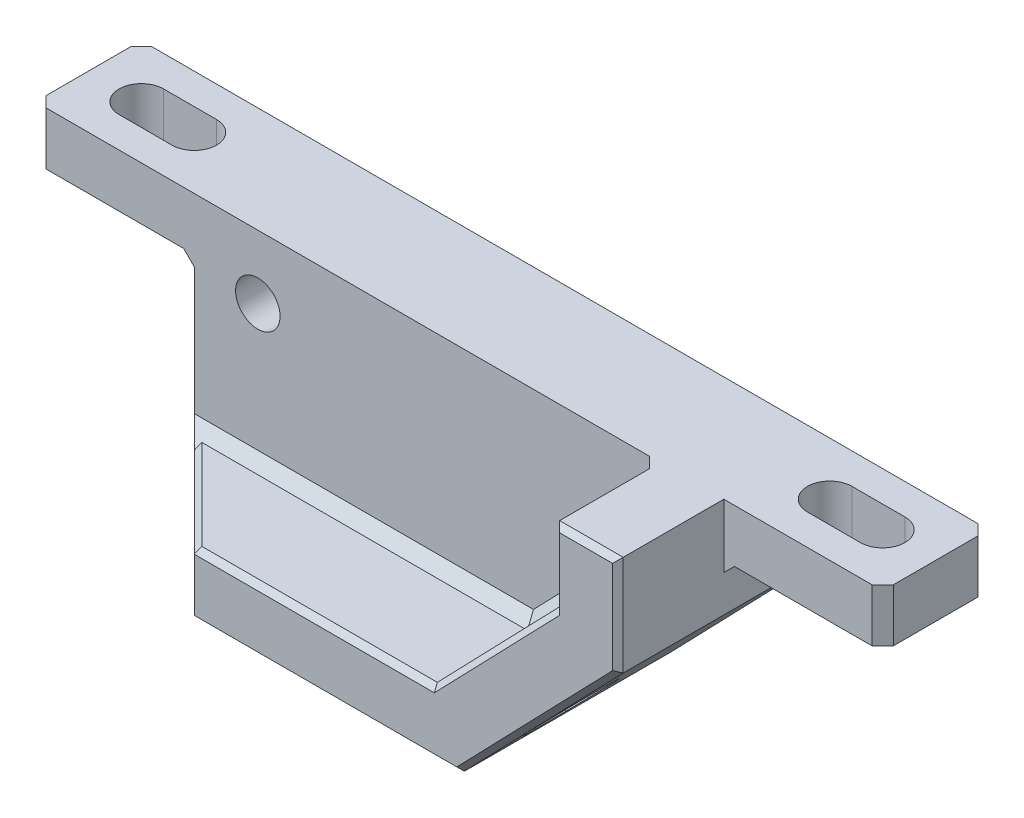
SolidWorks part; units mm, degrees
material "PET"
ref_plane "Přední rovina" through (0, 0, 0) normal (0, 0, 1) x (1, 0, 0)
ref_plane "Horní rovina" through (0, 0, 0) normal (0, 1, 0) x (1, 0, 0)
ref_plane "Pravá rovina" through (0, 0, 0) normal (1, 0, 0) x (0, 0, -1)
sketch "Skica1" plane through (0, 0, 0) normal (0, 0, 1) x (1, 0, 0)
  line L1 (0, 0) -> (50, 0)
  line L2 (0, 0) -> (0, 25)
  line L3 (0, 25) -> (50, 25)
  line L4 (50, 0) -> (50, 25)
  line L5 (0, 0) -> (50, 25) construction
  line L6 (0, 25) -> (50, 0) construction
  point P4 (25, 12.5)
  dimension "D1" = 25
  dimension "D2" = 50
extrude "Přidat vysunutím1" add sketch "Skica1" along normal blind 10
sketch "Skica2" plane through (0, 0, 10) normal (0, 0, 1) x (1, 0, 0)
  line L0 (0, 0) -> (35, 0)
  line L1 (0, 0) -> (50, 0) construction
  line L2 (35, 0) -> (50, 15.533)
  line L3 (50, 0) -> (50, 25) construction
  line L5 (44, 17.9571) -> (32.4532, 6)
  line L6 (0, 0) -> (0, 6)
  line L7 (0, 25) -> (0, 0) construction
  line L8 (0, 6) -> (32.4532, 6)
  line L9 (44, 25) -> (44, 17.9571)
  line L10 (50, 25) -> (0, 25) construction
  line L11 (44, 25) -> (50, 25)
  line L13 (50, 15.533) -> (50, 25)
  dimension "D1" = 6
  dimension "D2" = 6
  dimension "D3" = 46
  dimension "D4" = 35
  dimension "D5" = 6
extrude "Přidat vysunutím2" add sketch "Skica2" along normal blind 10
sketch "Skica3" plane through (0, 0, 10) normal (0, 0, 1) x (1, 0, 0)
  line L0 (0, 25) -> (0, 6) construction
  line L1 (44, 25) -> (0, 25) construction
  circle A0 centre (6, 19) radius 2.1
  dimension "D1" = 4.2
  dimension "D2" = 6
  dimension "D3" = 6
extrude "Odebrat vysunutím1" cut sketch "Skica3" against normal blind 10
sketch "Skica4" plane through (0, 0, 10) normal (0, 0, 1) x (1, 0, 0)
  line L3 (50, 15.533) -> (35, 0)
  line L4 (35, 0) -> (50, 0)
  line L5 (50, 0) -> (50, 15.533)
  line L6 (50, 15.533) -> (35, 0)
  line L7 (35, 0) -> (50, 0)
  line L8 (50, 0) -> (50, 15.533)
  dimension "D1" = 0
extrude "Odebrat vysunutím2" cut sketch "Skica4" against normal up to surface (10 mm away) up to face at (8.1, 19, 0)
sketch "Skica5" plane through (18.1107, -17.4893, 0) normal (0.7193, -0.6947, 0) x (0, 0, -1)
  line L3 (-20, 24.313) -> (0, 24.313) construction
  line L4 (-20, 24.313) -> (-20, 45.9064) construction
  circle A0 centre (-15, 32.313) radius 2.1
  dimension "D1" = 8
  dimension "D3" = 4.2
  dimension "D2" = 5
extrude "Odebrat vysunutím3" cut sketch "Skica5" against normal blind 10
sketch "Skica6" plane through (0, 25, 0) normal (0, 1, 0) x (1, 0, 0)
  line L0 (50, -20) -> (50, 0) construction
  line L5 (0, -10) -> (-15, -10)
  line L6 (0, -10) -> (0, 0)
  line L11 (0, 0) -> (-15, 0)
  line L12 (-15, -10) -> (-15, 0)
  line L13 (0, -10) -> (-15, 0) construction
  line L14 (0, 0) -> (-15, -10) construction
  line L15 (50, -10) -> (65, -10)
  line L16 (50, -10) -> (50, 0)
  line L17 (50, 0) -> (65, 0)
  line L18 (65, -10) -> (65, 0)
  line L19 (50, -10) -> (65, 0) construction
  line L20 (50, 0) -> (65, -10) construction
  line L21 (50, 0) -> (0, 0) construction
  point P4 (-7.5, -5)
  point P10 (57.5, -5)
  dimension "D3" = 15
  dimension "D1" = 10
  dimension "D2" = 15
  dimension "D4" = 10
extrude "Přidat vysunutím3" add sketch "Skica6" against normal blind 5
sketch "Skica9" plane through (18.1107, -17.4893, 0) normal (0.7193, -0.6947, 0) x (0, 0, -1)
  line L1 (-19.1569, 32.313) -> (-17.0785, 28.713)
  line L2 (-17.0785, 28.713) -> (-12.9215, 28.713)
  line L3 (-12.9215, 28.713) -> (-10.8431, 32.313)
  line L4 (-10.8431, 32.313) -> (-12.9215, 35.913)
  line L5 (-12.9215, 35.913) -> (-17.0785, 35.913)
  line L6 (-17.0785, 35.913) -> (-19.1569, 32.313)
  circle A0 centre (-15, 32.313) radius 3.6 construction
  dimension "D1" = 7.2
extrude "Odebrat vysunutím5" cut sketch "Skica9" against normal blind 3.5
sketch "Skica10" plane through (0, 0, 0) normal (0, 0, -1) x (-1, 0, 0)
  line L7 (-6, 23.1569) -> (-9.6, 21.0785)
  line L8 (-9.6, 21.0785) -> (-9.6, 16.9215)
  line L9 (-9.6, 16.9215) -> (-6, 14.8431)
  line L10 (-6, 14.8431) -> (-2.4, 16.9215)
  line L11 (-2.4, 16.9215) -> (-2.4, 21.0785)
  line L12 (-2.4, 21.0785) -> (-6, 23.1569)
  circle A0 centre (-6, 19) radius 3.6 construction
  dimension "D1" = 7.2
extrude "Odebrat vysunutím6" cut sketch "Skica10" against normal blind 4
chamfer "Zkosení1" distance 10 angle 45 1 edges at (0, 3, 20)
sketch "Skica11" plane through (0, 20, 0) normal (0, -1, 0) x (1, 0, 0)
  line L0 (-15, 5) -> (65, 5) construction
  line L1 (-15, 0) -> (-15, 10) construction
  line L2 (65, 10) -> (65, 0) construction
  line L3 (-10, 5) -> (-5, 5) construction
  line L4 (-10, 7.1) -> (-5, 7.1)
  line L5 (-10, 2.9) -> (-5, 2.9)
  line L6 (0, 10) -> (0, 0) construction
  line L7 (55, 5) -> (60, 5) construction
  line L8 (55, 7.1) -> (60, 7.1)
  line L9 (55, 2.9) -> (60, 2.9)
  line L11 (50, 20) -> (50, 0) construction
  arc A2 (-10, 7.1) -> (-10, 2.9) centre (-10, 5) ccw
  arc A3 (-5, 2.9) -> (-5, 7.1) centre (-5, 5) ccw
  arc A4 (55, 7.1) -> (55, 2.9) centre (55, 5) ccw
  arc A5 (60, 2.9) -> (60, 7.1) centre (60, 5) ccw
  point P10 (-7.5, 5)
  point P17 (57.5, 5)
  dimension "D1" = 4.2
  dimension "D2" = 4.2
  dimension "D6" = 5
  dimension "D3" = 5
  dimension "D4" = 5
  dimension "D5" = 5
extrude "Odebrat vysunutím7" cut sketch "Skica11" against normal up to surface (5 mm away) up to face at (36, 25, 10)
chamfer "Zkosení3" distance 1 angle 45 3 edges at (44, 21.4786, 10) (38.2266, 11.9786, 10) (16.2266, 6, 10)
chamfer "Zkosení4" distance 0.5 angle 45 9 edges at (5.5, 6, 15.5) (21.2266, 6, 20) (38.2266, 11.9786, 20) (44, 21.4786, 20) (47, 25, 20) (50, 20.2665, 20) (42.5, 7.7665, 20) (5, 0, 15) (22.5, 0, 20)
chamfer "Zkosení5" distance 1 angle 45 2 edges at (50, 20, 5) (0, 20, 5)
chamfer "Zkosení7" distance 1 angle 45 4 edges at (65, 22.5, 10) (-15, 22.5, 10) (65, 22.5, 0) (-15, 22.5, 0)
